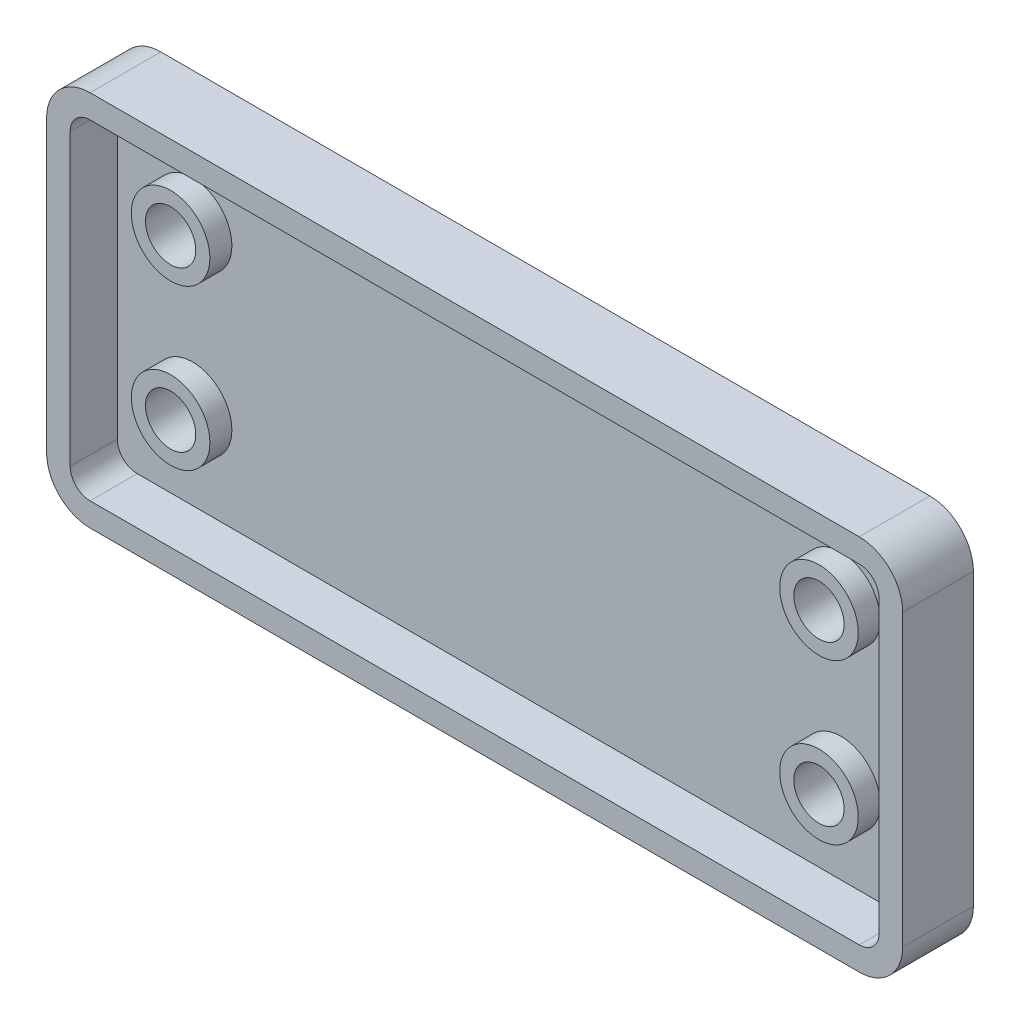
SolidWorks part; units mm, degrees
material "Plastique personnalisé"
ref_plane "Plan de face" through (0, 0, 0) normal (0, 0, 1) x (1, 0, 0)
ref_plane "Plan de dessus" through (0, 0, 0) normal (0, 1, 0) x (1, 0, 0)
ref_plane "Plan de droite" through (0, 0, 0) normal (1, 0, 0) x (0, 0, -1)
sketch "Esquisse1" plane through (0, 0, 0) normal (0, 0, 1) x (1, 0, 0)
  line L1 (-24.48, -10.5) -> (24.48, -10.5)
  line L2 (-25.75, -9.23) -> (-25.75, 9.23)
  line L3 (-24.48, 10.5) -> (24.48, 10.5)
  line L4 (25.75, -9.23) -> (25.75, 9.23)
  line L5 (-25.75, -10.5) -> (25.75, 10.5) construction
  line L6 (-25.75, 10.5) -> (25.75, -10.5) construction
  arc A0 (24.48, -10.5) -> (25.75, -9.23) centre (24.48, -9.23) ccw
  arc A1 (-24.48, -10.5) -> (-25.75, -9.23) centre (-24.48, -9.23) cw
  arc A2 (-25.75, 9.23) -> (-24.48, 10.5) centre (-24.48, 9.23) cw
  arc A3 (24.48, 10.5) -> (25.75, 9.23) centre (24.48, 9.23) cw
  point P0 (0, 0)
  dimension "D3" = 1.27
  dimension "D1" = 51.5
  dimension "D2" = 21
extrude "Boss.-Extru.1" add sketch "Esquisse1" along normal blind 3
shell "Coque1" thickness 1.5
ref_plane "PlanMedian" through (0, 0, 0) normal (0, 1, 0) x (1, 0, 0)
ref_plane "PlanSagital" through (0, 0, 0) normal (-1, 0, 0) x (0, 0, 1)
sketch "Esquisse2" plane through (0, 0, 0) normal (0, 0, 1) x (1, 0, 0)
  circle A0 centre (-20.955, 5.08) radius 1.6
  circle A1 centre (-20.955, -5.08) radius 1.6
  circle A2 centre (20.32, 5.08) radius 1.6
  circle A3 centre (20.32, -5.08) radius 1.6
  circle A5 centre (20.32, 5.08) radius 2.5
  circle A6 centre (-20.955, -5.08) radius 2.5
  circle A7 centre (-20.955, 5.08) radius 2.5
  circle A8 centre (20.32, -5.08) radius 2.5
  dimension "D1" = 5
extrude "Boss.-Extru.2" add sketch "Esquisse2" along normal blind 1.4
sketch "Esquisse3" plane through (0, 0, 0) normal (0, 0, 1) x (1, 0, 0)
  circle A0 centre (20.32, 5.08) radius 1.6
  circle A1 centre (-20.955, 5.08) radius 1.6
  circle A2 centre (-20.955, -5.08) radius 1.6
  circle A3 centre (20.32, -5.08) radius 1.6
extrude "Enlèv. mat.-Extru.1" cut sketch "Esquisse3" against normal through all both and the other way through all
